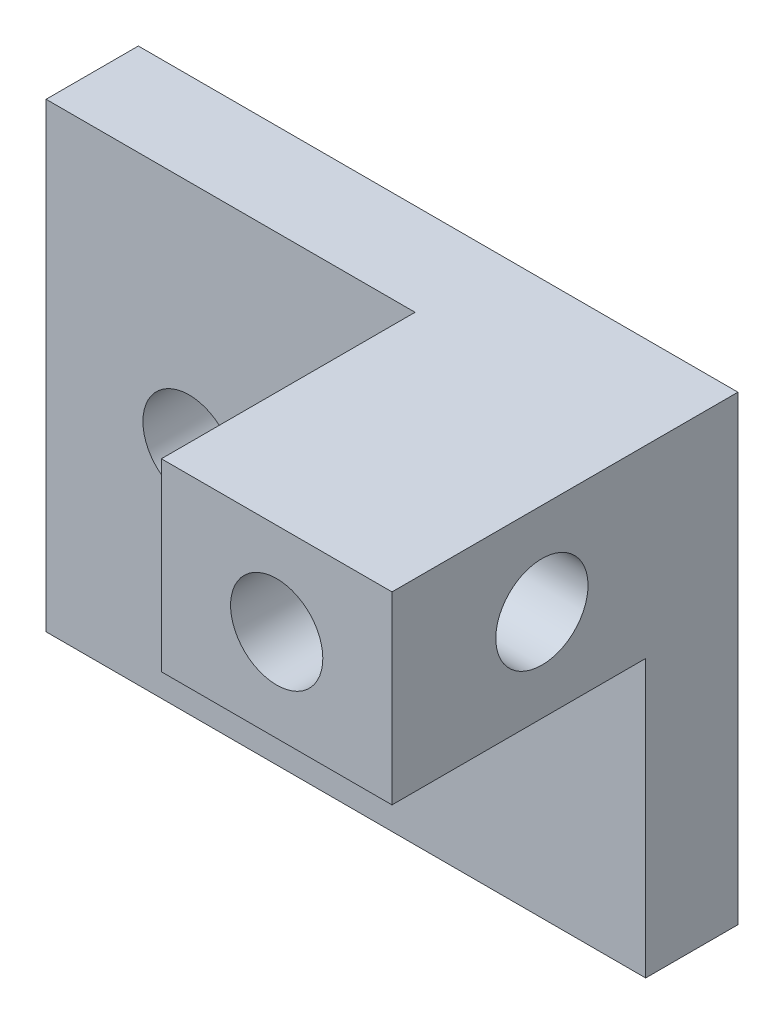
SolidWorks part; units mm, degrees
ref_plane "Спереди" through (0, 0, 0) normal (0, 0, 1) x (1, 0, 0)
ref_plane "Сверху" through (0, 0, 0) normal (0, 1, 0) x (1, 0, 0)
ref_plane "Справа" through (0, 0, 0) normal (1, 0, 0) x (0, 0, -1)
sketch "Эскиз1" plane through (0, 0, 0) normal (0, 0, 1) x (1, 0, 0)
  line L1 (-65, -50) -> (65, -50)
  line L2 (-65, -50) -> (-65, 50)
  line L3 (-65, 50) -> (65, 50)
  line L4 (65, -50) -> (65, 50)
  line L5 (-65, -50) -> (65, 50) construction
  line L6 (-65, 50) -> (65, -50) construction
  point P0 (0, 0)
  dimension "D1" = 130
  dimension "D2" = 100
extrude "Бобышка-Вытянуть1" add sketch "Эскиз1" along normal blind 20
sketch "Эскиз2" plane through (0, 0, 20) normal (0, 0, 1) x (1, 0, 0)
  line L0 (-65, 0) -> (65, 0) construction
  line L1 (-65, 50) -> (-65, -50) construction
  line L2 (65, -50) -> (65, 50) construction
  line L3 (65, 50) -> (-65, 50) construction
  line L4 (-7, -38) -> (53, -38)
  line L5 (-7, -38) -> (-7, 38)
  line L6 (-7, 38) -> (53, 38)
  line L7 (53, -38) -> (53, 38)
  line L8 (-7, -38) -> (53, 38) construction
  line L9 (-7, 38) -> (53, -38) construction
  line L11 (-53, -38) -> (-15, -38)
  line L12 (-53, -38) -> (-53, 38)
  line L13 (-53, 38) -> (-15, 38)
  line L14 (-15, -38) -> (-15, 38)
  line L15 (-53, -38) -> (-15, 38) construction
  line L16 (-53, 38) -> (-15, -38) construction
  point P6 (23, 0)
  point P13 (-34, 0)
  dimension "D1" = 12
  dimension "D2" = 12
  dimension "D3" = 60
  dimension "D4" = 12
  dimension "D5" = 8
extrude "Вырез-Вытянуть1" cut sketch "Эскиз2" against normal blind 10
sketch "Эскиз3" plane through (0, 0, 10) normal (0, 0, 1) x (1, 0, 0)
  line L1 (65, 50) -> (15, 50)
  line L2 (65, 50) -> (65, 10)
  line L3 (65, 10) -> (15, 10)
  line L4 (15, 50) -> (15, 10)
  dimension "D1" = 50
  dimension "D2" = 40
extrude "Бобышка-Вытянуть2" add sketch "Эскиз3" along normal blind 65
sketch "Эскиз4" plane through (0, 0, 10) normal (0, 0, 1) x (1, 0, 0)
  line L0 (-34, 38) -> (-34, -38) construction
  line L1 (-15, 38) -> (-53, 38) construction
  line L2 (-53, -38) -> (-15, -38) construction
  circle A0 centre (-34, 0) radius 10
  dimension "D1" = 20
extrude "Вырез-Вытянуть2" cut sketch "Эскиз4" against normal through all
sketch "Эскиз5" plane through (15, 0, 0) normal (-1, 0, 0) x (0, 0, 1)
  line L0 (75, 30) -> (10, 30) construction
  line L1 (75, 50) -> (75, 10) construction
  line L2 (10, 38) -> (10, 10) construction
  circle A0 centre (42.5, 30) radius 10
  dimension "D1" = 20
extrude "Вырез-Вытянуть3" cut sketch "Эскиз5" against normal through all
sketch "Эскиз6" plane through (0, 0, 75) normal (0, 0, 1) x (1, 0, 0)
  line L0 (15, 30) -> (65, 30) construction
  line L1 (15, 50) -> (15, 10) construction
  line L2 (65, 10) -> (65, 50) construction
  circle A0 centre (40, 30) radius 10
  dimension "D1" = 20
extrude "Вырез-Вытянуть4" cut sketch "Эскиз6" against normal through all
sketch "Эскиз7" plane through (0, 0, 10) normal (0, 0, 1) x (1, 0, 0)
  line L4 (-15, -38) -> (-15, 38)
  line L5 (-15, 38) -> (-53, 38)
  line L6 (15, 10) -> (15, 38)
  line L7 (15, 38) -> (-7, 38)
  line L8 (-7, 38) -> (-7, -38)
  line L9 (-7, -38) -> (53, -38)
  line L10 (53, -38) -> (53, 10)
  line L11 (53, 10) -> (15, 10)
  line L12 (15, 10) -> (15, 38)
  line L13 (15, 38) -> (-7, 38)
  line L14 (-7, 38) -> (-7, -38)
  line L15 (-7, -38) -> (53, -38)
  line L16 (53, -38) -> (53, 10)
  line L17 (53, 10) -> (15, 10)
  line L18 (-53, 38) -> (-53, -38)
  line L19 (-53, -38) -> (-15, -38)
  line L20 (-15, -38) -> (-15, 38)
  line L21 (-15, 38) -> (-53, 38)
  line L22 (-53, 38) -> (-53, -38)
  line L23 (-53, -38) -> (-15, -38)
  circle A0 centre (-34, 0) radius 10 construction
  circle A1 centre (-34, 0) radius 10
  dimension "D1" = 0
  dimension "D2" = 0
extrude "Бобышка-Вытянуть3" add sketch "Эскиз7" along normal up to surface (10 mm away) up to face at (-34, 0, 20)
